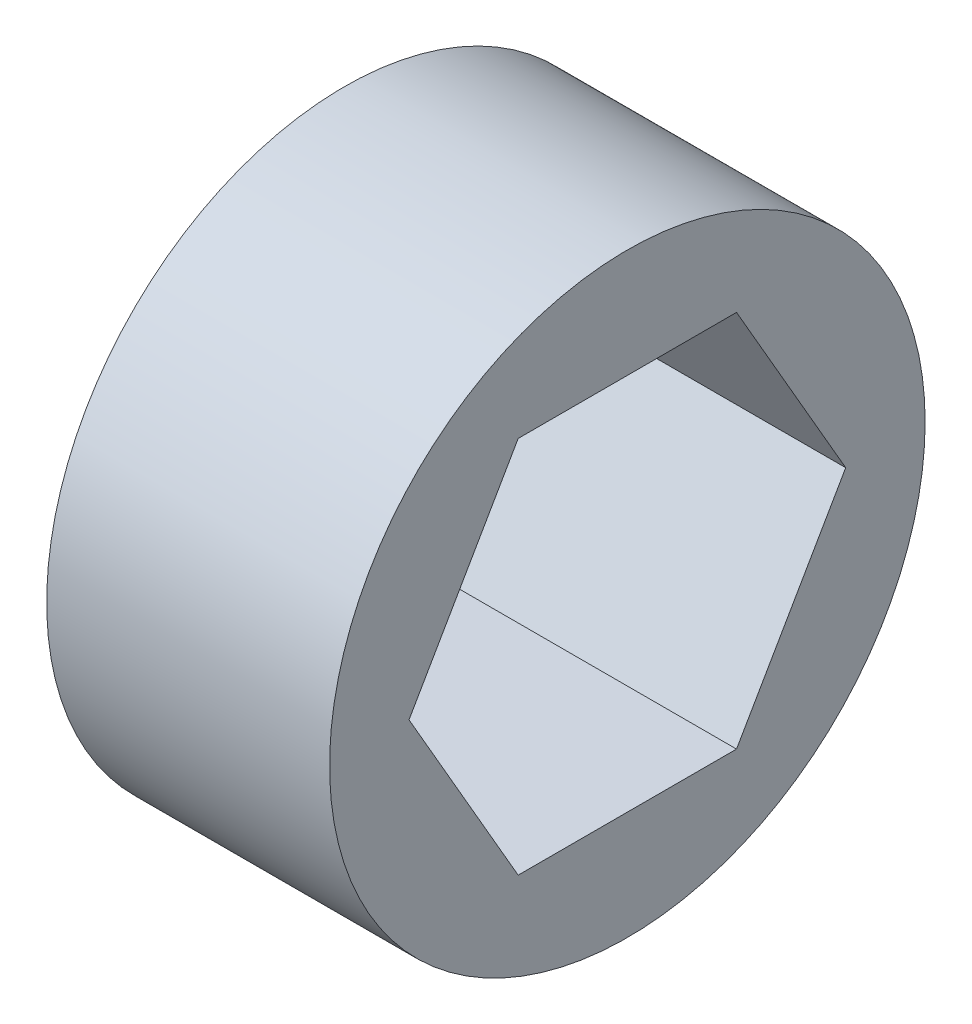
SolidWorks part; units mm, degrees
ref_plane "Alzado" through (0, 0, 0) normal (0, 0, 1) x (1, 0, 0)
ref_plane "Planta" through (0, 0, 0) normal (0, 1, 0) x (1, 0, 0)
ref_plane "Vista lateral" through (0, 0, 0) normal (1, 0, 0) x (0, 0, -1)
sketch "Croquis1" plane through (0, 0, 0) normal (1, 0, 0) x (0, 0, -1)
  line L1 (7.3323, 0) -> (3.6662, 6.35)
  line L2 (3.6662, 6.35) -> (-3.6662, 6.35)
  line L3 (-3.6662, 6.35) -> (-7.3323, 0)
  line L4 (-7.3323, 0) -> (-3.6662, -6.35)
  line L5 (-3.6662, -6.35) -> (3.6662, -6.35)
  line L6 (3.6662, -6.35) -> (7.3323, 0)
  circle A0 centre (0, 0) radius 10
  circle A1 centre (0, 0) radius 6.35 construction
  dimension "D1" = 20
extrude "Saliente-Extruir1" add sketch "Croquis1" along normal blind 9.5
